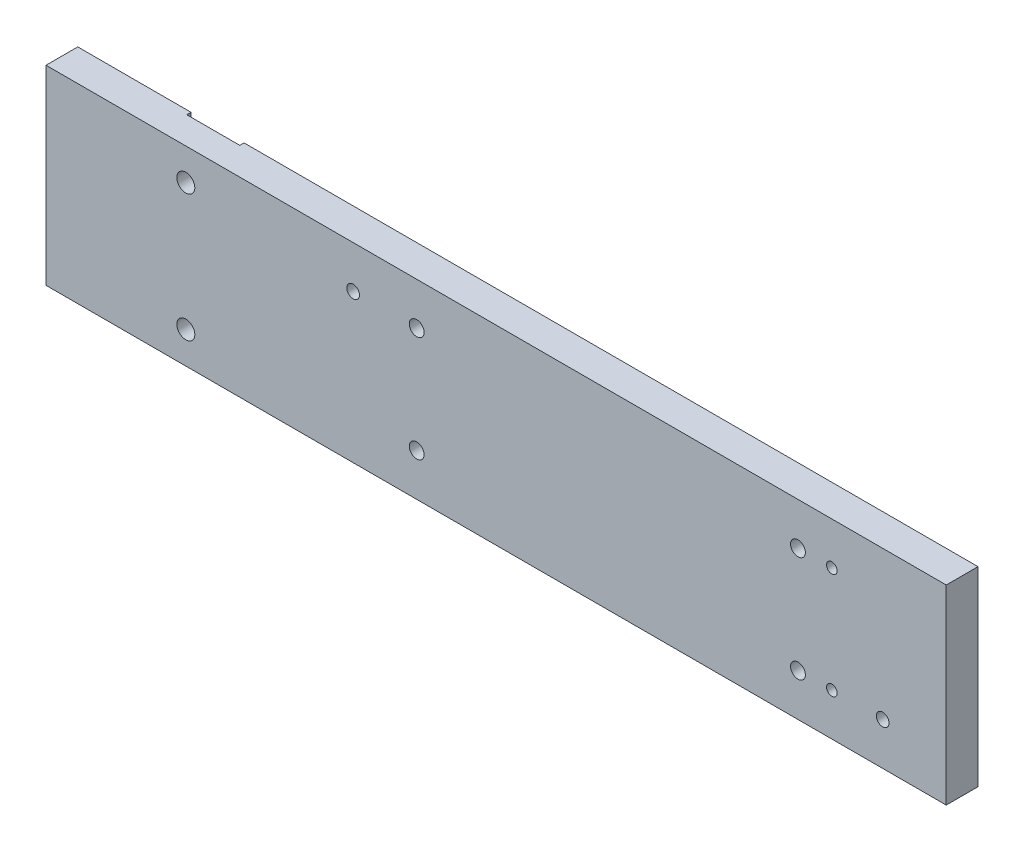
SolidWorks part; units mm, degrees
material "SKD11淬火HRC56-60"
ref_plane "前基準面" through (0, 0, 0) normal (0, 0, 1) x (1, 0, 0)
ref_plane "上基準面" through (0, 0, 0) normal (0, 1, 0) x (1, 0, 0)
ref_plane "右基準面" through (0, 0, 0) normal (1, 0, 0) x (0, 0, -1)
sketch "草图1" plane through (0, 0, 0) normal (0, 0, 1) x (1, 0, 0)
  line L1 (0, 0) -> (425, 0)
  line L2 (0, 0) -> (0, 90)
  line L3 (0, 90) -> (425, 90)
  line L4 (425, 0) -> (425, 90)
  dimension "D1" = 90
  dimension "D2" = 425
extrude "凸台-拉伸1" add sketch "草图1" along normal blind 15
sketch "草图2" plane through (0, 90, 0) normal (0, 1, 0) x (1, 0, 0)
  line L0 (425, 0) -> (0, 0) construction
  line L1 (53.5, 0) -> (78.5, 0)
  line L2 (53.5, 0) -> (53.5, -2)
  line L3 (53.5, -2) -> (78.5, -2)
  line L4 (78.5, 0) -> (78.5, -2)
  line L5 (0, -15) -> (0, 0) construction
  dimension "D1" = 2
  dimension "D2" = 25
  dimension "D3" = 53.5
extrude "切除-拉伸1" cut sketch "草图2" against normal through all
hole_wizard "M10 螺纹孔1" positions "草图4" profile "草图3" tap size "M10" standard "ISO"
sketch "草图4" plane through (0, 0, 2) normal (0, 0, -1) x (-1, 0, 0)
  point P0 (-66, 75)
  point P1 (-66, 15)
sketch "草图3" plane through (66, 75, 2) normal (1, 0, 0) x (0, 1, 0)
  line L0 (0, 0) -> (0, 27.0537)
  line L1 (0, 27.0537) -> (4.25, 24.5)
  line L2 (4.25, 24.5) -> (4.25, 0)
  line L5 (4.25, 0) -> (0, 0)
  line L10 (0, 27.0537) -> (-4.25, 24.5) construction
  line L11 (0, -6.35) -> (0, 107.95) construction
  dimension "螺纹孔钻头直径" = 8.5
  dimension "螺纹孔钻头深度" = 24.5
  dimension "导头角度" = 118
cosmetic thread "孔螺蚊线1" parameters "D1"=13, "D2"=10
cosmetic thread "孔螺蚊线2" parameters "D1"=13, "D2"=10
hole_wizard "M6 螺纹孔1" positions "草图6" profile "草图5" tap size "M6" standard "ISO"
sketch "草图6" plane through (0, 0, 0) normal (-1, 0, 0) x (0, 0, 1)
  point P0 (7.5, 68)
  point P1 (7.5, 22)
sketch "草图5" plane through (0, 68, 7.5) normal (0, 1, 0) x (0, 0, 1)
  line L0 (0, 0) -> (0, 16.5022)
  line L1 (0, 16.5022) -> (2.5, 15)
  line L2 (2.5, 15) -> (2.5, 0)
  line L5 (2.5, 0) -> (0, 0)
  line L10 (0, 16.5022) -> (-2.5, 15) construction
  line L11 (0, -6.35) -> (0, 107.95) construction
  dimension "螺纹孔钻头直径" = 5
  dimension "螺纹孔钻头深度" = 15
  dimension "导头角度" = 118
cosmetic thread "孔螺蚊线3" parameters "D1"=12, "D2"=6
cosmetic thread "孔螺蚊线4" parameters "D1"=12, "D2"=6
hole_wizard "M5 螺纹孔1" positions "草图8" profile "草图7" tap size "M5" standard "ISO"
sketch "草图8" plane through (0, 0, 0) normal (0, -1, 0) x (1, 0, 0)
  point P0 (9, 8)
  point P1 (44, 8)
sketch "草图7" plane through (9, 0, 8) normal (1, 0, 0) x (0, 0, -1)
  line L0 (0, 0) -> (0, 13.6618)
  line L1 (0, 13.6618) -> (2.1, 12.4)
  line L2 (2.1, 12.4) -> (2.1, 0)
  line L5 (2.1, 0) -> (0, 0)
  line L10 (0, 13.6618) -> (-2.1, 12.4) construction
  line L11 (0, -6.35) -> (0, 107.95) construction
  dimension "螺纹孔钻头直径" = 4.2
  dimension "螺纹孔钻头深度" = 12.4
  dimension "导头角度" = 118
cosmetic thread "孔螺蚊线5" parameters "D1"=10, "D2"=5
cosmetic thread "孔螺蚊线6" parameters "D1"=10, "D2"=5
hole_wizard "M6 螺纹孔2" positions "草图10" profile "草图9" tap size "M6" standard "ISO"
sketch "草图10" plane through (0, 0, 0) normal (0, 0, -1) x (-1, 0, 0)
  point P0 (-371, 70)
  point P1 (-371, 20)
sketch "草图9" plane through (371, 70, 0) normal (1, 0, 0) x (0, 1, 0)
  line L0 (0, 0) -> (0, 16.5022)
  line L1 (0, 16.5022) -> (2.5, 15)
  line L2 (2.5, 15) -> (2.5, 0)
  line L5 (2.5, 0) -> (0, 0)
  line L10 (0, 16.5022) -> (-2.5, 15) construction
  line L11 (0, -6.35) -> (0, 107.95) construction
  dimension "螺纹孔钻头直径" = 5
  dimension "螺纹孔钻头深度" = 15
  dimension "导头角度" = 118
cosmetic thread "孔螺蚊线7" parameters "D1"=12, "D2"=6
cosmetic thread "孔螺蚊线8" parameters "D1"=12, "D2"=6
sketch "草图11" plane through (0, 0, 0) normal (0, 0, -1) x (-1, 0, 0)
  line L0 (-425, 0) -> (-425, 90) construction
  line L1 (-78.5, 0) -> (-425, 0) construction
  circle A0 centre (-145, 70) radius 3
  circle A1 centre (-395, 20) radius 3
  dimension "D1" = 6
  dimension "D2" = 30
  dimension "D3" = 20
  dimension "D4" = 250
  dimension "D5" = 70
extrude "切除-拉伸2" cut sketch "草图11" against normal through all
hole_wizard "M6 六角凹头螺钉的柱形沉头孔1" positions "草图13" profile "草图12" counterbore size "M6" standard "ISO" end condition through all
sketch "草图13" plane through (0, 0, 0) normal (0, 0, -1) x (-1, 0, 0)
  line L0 (-78.5, 0) -> (-425, 0) construction
  line L1 (-425, 90) -> (-78.5, 90) construction
  line L2 (-425, 0) -> (-425, 90) construction
  point P0 (-175, 20)
  point P1 (-355, 20)
  point P3 (-175, 70)
  point P5 (-355, 70)
  dimension "D1" = 20
  dimension "D2" = 20
  dimension "D3" = 70
  dimension "D4" = 180
sketch "草图12" plane through (175, 20, 0) normal (1, 0, 0) x (0, 1, 0)
  line L0 (0, 0) -> (0, 15)
  line L1 (0, 15) -> (3.5, 15)
  line L3 (3.5, 15) -> (3.5, 6)
  line L4 (3.5, 6) -> (5.5, 6)
  line L5 (5.5, 6) -> (5.5, 0)
  line L7 (5.5, 0) -> (0, 0)
  line L11 (0, -6.35) -> (0, 107.95) construction
  dimension "通孔孔直径" = 7
  dimension "通孔孔深度" = 15
  dimension "柱形沉头孔直径" = 11
  dimension "柱形沉头孔深度" = 6
